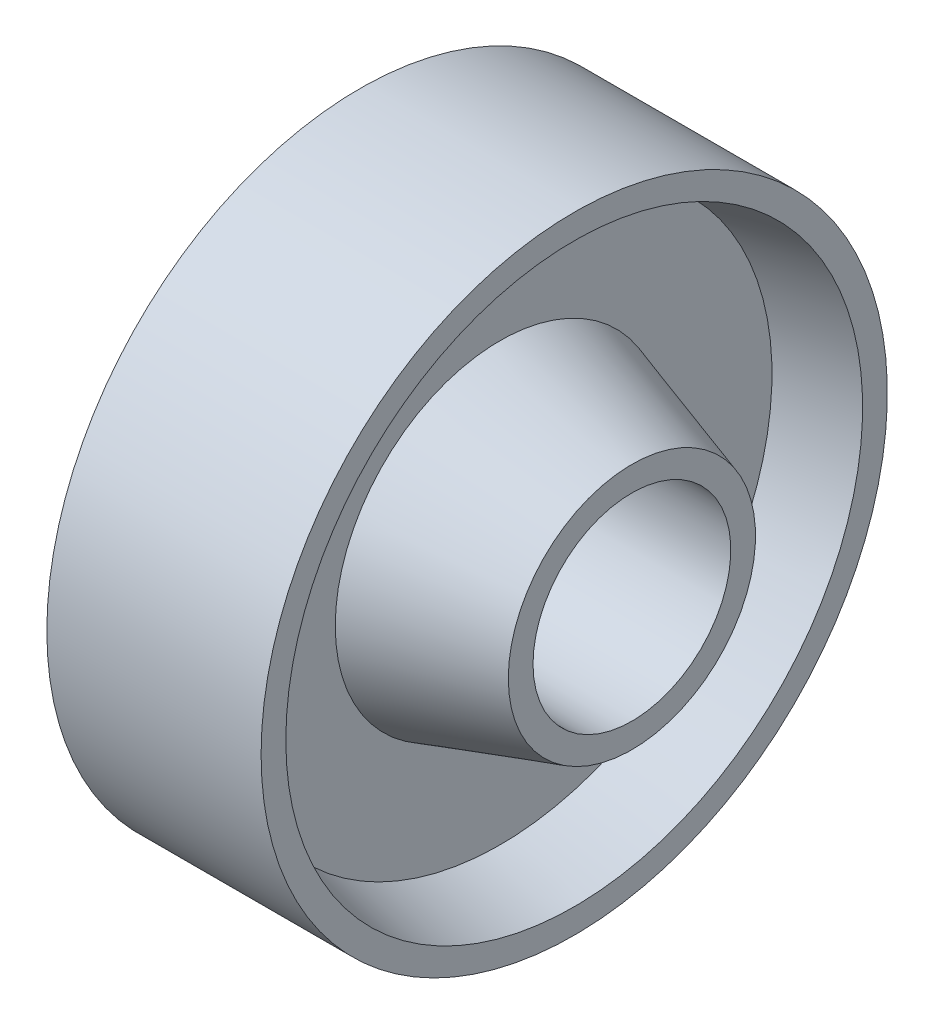
SolidWorks part; units mm, degrees
ref_plane "Front Plane" through (0, 0, 0) normal (0, 0, 1) x (1, 0, 0)
ref_plane "Top Plane" through (0, 0, 0) normal (0, 1, 0) x (1, 0, 0)
ref_plane "Right Plane" through (0, 0, 0) normal (1, 0, 0) x (0, 0, -1)
sketch "Sketch1" plane through (0, 0, 0) normal (0, 0, 1) x (1, 0, 0)
  line L0 (0, 0) -> (92.5738, 0) construction
  line L9 (0, 12) -> (40, 12)
  line L13 (33, 38) -> (7, 38)
  line L15 (16, 33) -> (16, 20)
  line L17 (40, 12) -> (40, 15)
  line L18 (40, 15) -> (24, 20)
  line L19 (0, 12) -> (0, 15)
  line L20 (0, 15) -> (16, 20)
  line L23 (7, 38) -> (7, 35)
  line L24 (7, 35) -> (16, 33)
  line L25 (33, 38) -> (33, 35)
  line L26 (33, 35) -> (24, 33)
  line L27 (24, 33) -> (24, 20)
  point P5 (0, 0)
  point P17 (0, 0)
  point P18 (0, 0)
  point P19 (0, 0)
  point P20 (20, 38)
  dimension "D1" = 40
  dimension "D2" = 12
  dimension "D3" = 20
  dimension "D4" = 20
  dimension "D5" = 15
  dimension "D6" = 15
  dimension "D7" = 8
  dimension "D8" = 26
  dimension "D9" = 20
  dimension "D10" = 4
  dimension "D11" = 38
  dimension "D12" = 35
  dimension "D13" = 33
revolve "Revolve1" add sketch "Sketch1" angle 360 about L0
